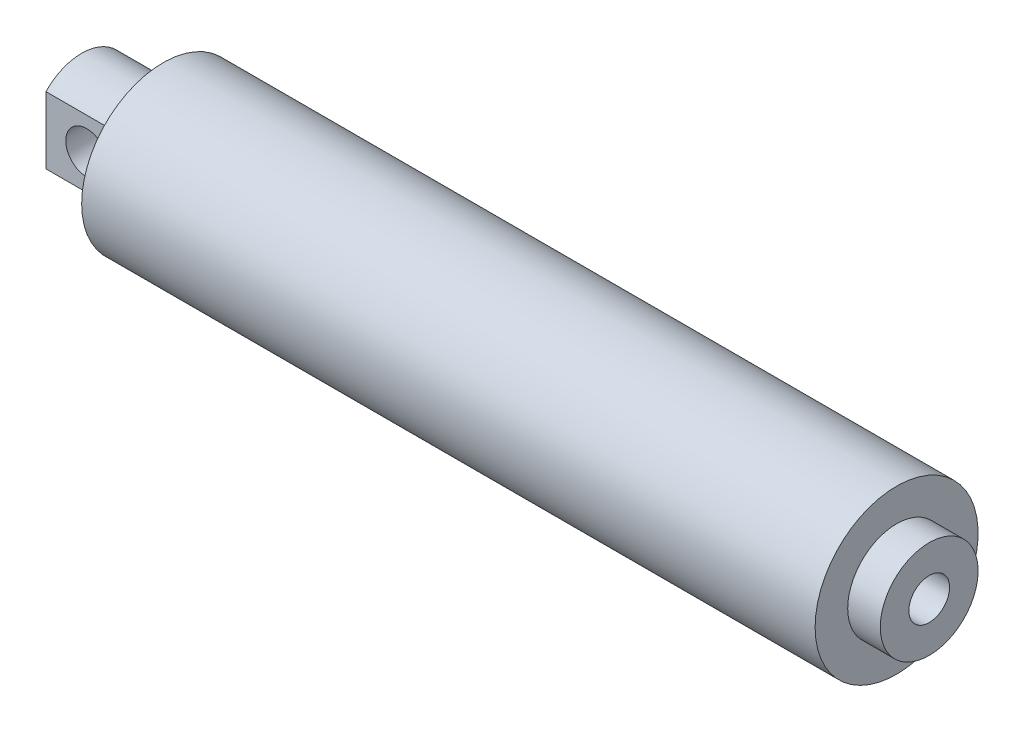
SolidWorks part; units mm, degrees
ref_plane "Front Plane" through (0, 0, 0) normal (0, 0, 1) x (1, 0, 0)
ref_plane "Top Plane" through (0, 0, 0) normal (0, 1, 0) x (1, 0, 0)
ref_plane "Right Plane" through (0, 0, 0) normal (1, 0, 0) x (0, 0, -1)
sketch "Sketch1" plane through (0, 0, 0) normal (0, 0, 1) x (1, 0, 0)
  line L0 (0, 0) -> (0, 5.08)
  line L1 (0, 25.4) -> (114.3, 25.4)
  line L2 (114.3, 25.4) -> (114.3, 20.32)
  line L3 (114.3, 0) -> (0, 0)
  line L4 (0, 5.08) -> (-12.7, 5.08)
  line L5 (-12.7, 5.08) -> (-12.7, 20.32)
  line L6 (-12.7, 20.32) -> (0, 20.32)
  line L7 (0, 20.32) -> (0, 25.4)
  line L8 (114.3, 20.32) -> (119.38, 20.32)
  line L9 (119.38, 20.32) -> (119.38, 5.08)
  line L10 (119.38, 5.08) -> (114.3, 5.08)
  line L11 (114.3, 5.08) -> (114.3, 0)
  line L12 (-12.7, 12.7) -> (119.38, 12.7) construction
  dimension "D1" = 114.3
  dimension "D2" = 12.7
  dimension "D3" = 15.24
  dimension "D4" = 5.08
  dimension "D5" = 25.4
  dimension "D6" = 15.24
  dimension "D7" = 5.08
revolve "Revolve2" add sketch "Sketch1" angle 360 about L12
sketch "Sketch2" plane through (119.38, 0, 0) normal (1, 0, 0) x (0, 0, -1)
  circle A0 centre (0, 12.7) radius 3.175
  circle A1 centre (0, 12.7) radius 7.62 construction
  dimension "D1" = 6.35
extrude "Cut-Extrude1" cut sketch "Sketch2" against normal blind 101.6
sketch "Sketch3" plane through (-12.7, 0, 0) normal (-1, 0, 0) x (0, 0, 1)
  line L0 (-5.5562, 20.32) -> (5.5562, 20.32) construction
  line L1 (-5.5562, 20.32) -> (-8.0962, 20.32)
  line L2 (-5.5562, 20.32) -> (-5.5562, 5.492)
  line L3 (-5.5562, 5.492) -> (-8.0962, 5.492)
  line L4 (-8.0962, 20.32) -> (-8.0962, 5.492)
  line L5 (5.5562, 20.32) -> (8.0962, 20.32)
  line L6 (5.5562, 20.32) -> (5.5563, 6.0638)
  line L7 (5.5563, 6.0638) -> (8.0963, 6.0638)
  line L8 (8.0962, 20.32) -> (8.0963, 6.0638)
  line L9 (0, 20.32) -> (0, 0) construction
  dimension "D1" = 11.1125
  dimension "D2" = 2.54
  dimension "D3" = 2.54
extrude "Cut-Extrude2" cut sketch "Sketch3" against normal blind 12.7
sketch "Sketch4" plane through (0, 0, 5.5563) normal (0, 0, 1) x (1, 0, 0)
  line L0 (-12.7, 17.9146) -> (-12.7, 7.4854) construction
  line L1 (0, 17.9146) -> (-12.7, 17.9146) construction
  circle A0 centre (-6.35, 12.8346) radius 3.2639
  dimension "D3" = 6.5278
  dimension "D1" = 6.35
  dimension "D2" = 5.08
extrude "Cut-Extrude3" cut sketch "Sketch4" against normal through all
